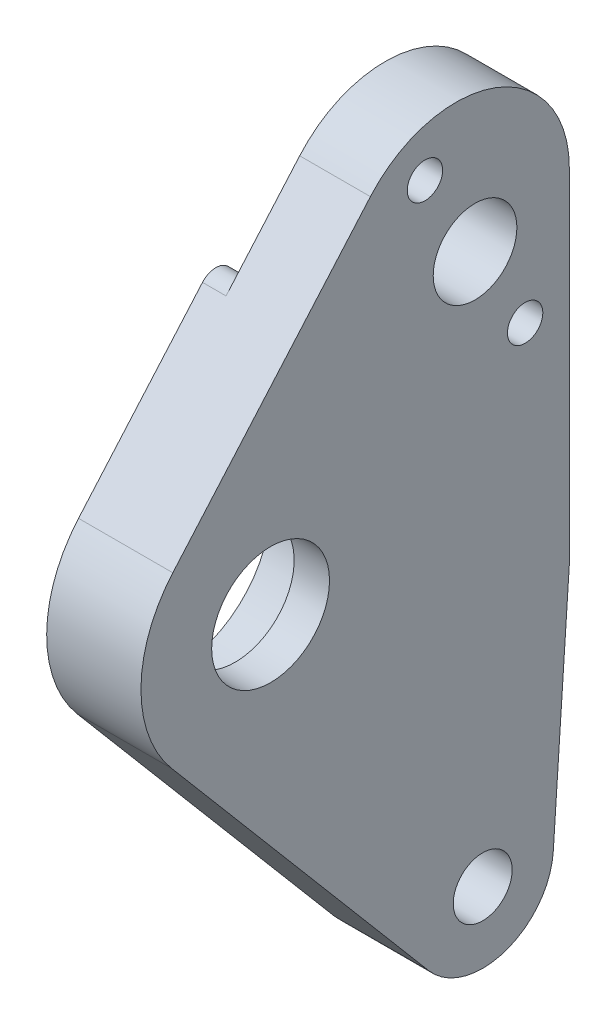
SolidWorks part; units mm, degrees
material "POM Acetal Copolymer"
ref_plane "Front Plane" through (0, 0, 0) normal (0, 0, 1) x (1, 0, 0)
ref_plane "Top Plane" through (0, 0, 0) normal (0, 1, 0) x (1, 0, 0)
ref_plane "Right Plane" through (0, 0, 0) normal (1, 0, 0) x (0, 0, -1)
sketch "Sketch27" plane through (0, 0, 0) normal (1, 0, 0) x (0, 0, -1)
  line L0 (3.7034, 44.2227) -> (20.4692, 63.4812)
  line L1 (37.3494, 57.163) -> (37.3494, 28)
  line L5 (37.3494, 28) -> (35.9867, 7.6001)
  line L6 (25.4207, 4.1232) -> (3.6046, 29.8925)
  line L8 (0, 0) -> (60, 0) construction
  line L9 (0, 0) -> (0, 58) construction
  line L10 (0, 58) -> (60, 58) construction
  line L11 (60, 0) -> (60, 58) construction
  arc A0 (3.7034, 44.2227) -> (3.6046, 29.8925) centre (12, 37) ccw
  circle A1 centre (29.3494, 55) radius 12.5 construction
  arc A2 (37.3494, 57.163) -> (20.4692, 63.4812) centre (27.7268, 57.163) ccw
  circle A3 centre (29.3494, 55) radius 3.55
  arc A4 (35.9867, 7.6001) -> (25.4207, 4.1232) centre (30, 8) cw
  circle A5 centre (12, 37) radius 5
  circle A6 centre (30, 8) radius 2.5
  dimension "D9" = 6
  dimension "D10" = 5
  dimension "D11" = 28
  dimension "D12" = 10
  dimension "D13" = 11
  dimension "D15" = 25
  dimension "D6" = 25
  dimension "D17" = 7.1
  dimension "D1" = 60
  dimension "D2" = 58
  dimension "D3" = 37
  dimension "D4" = 12
  dimension "D5" = 30
  dimension "D7" = 8
  dimension "D8" = 18
  dimension "D16" = 8
extrude "Boss-Extrude1" add sketch "Sketch27" along normal blind 8
hole_wizard "Tap Drill for M3 Tap2" positions "Sketch45" profile "Sketch44" hole size "M3" standard "ISO"
sketch "Sketch45" plane through (0, 0, -37.3494) normal (0, 0, -1) x (-1, 0, 0)
  line L3 (-8, 28) -> (0, 28) construction
  line L4 (-8, 28) -> (-8, 57.163) construction
  point P0 (-5, 44)
  point P7 (-5, 32)
  dimension "D1" = 4
  dimension "D2" = 3
  dimension "D3" = 12
sketch "Sketch44" plane through (5, 44, -37.3494) normal (1, 0, 0) x (0, 1, 0)
  line L0 (0, 0) -> (0, 10.7511)
  line L1 (0, 10.7511) -> (1.25, 10)
  line L2 (1.25, 10) -> (1.25, 0)
  line L5 (1.25, 0) -> (0, 0)
  line L10 (0, 10.7511) -> (-1.25, 10) construction
  line L11 (0, -6.35) -> (0, 107.95) construction
  dimension "Hole Dia." = 2.5
  dimension "Hole Depth" = 10
  dimension "Drill Angle" = 118
sketch "Sketch47" plane through (0, 0, 0) normal (-1, 0, 0) x (0, 0, 1)
  circle A0 centre (-12, 37) radius 7.99
  dimension "D1" = 15.98
extrude "Cut-Extrude8" cut sketch "Sketch47" against normal blind 5
sketch "Sketch48" plane through (0, 0, 0) normal (-1, 0, 0) x (0, 0, 1)
  line L0 (-37.3494, 28) -> (-37.3494, 57.163) construction
  line L1 (-20.4692, 63.4812) -> (-3.7034, 44.2227) construction
  line L2 (-37.3494, 42.6004) -> (-37.3494, 72.6467)
  line L3 (-37.3494, 72.6467) -> (-14.2217, 72.6467)
  line L4 (-14.2217, 72.6467) -> (-14.2217, 56.3048)
  arc A0 (-35.1529, 43.9289) -> (-16.8526, 55.2856) centre (-29.3494, 55) ccw
  arc A1 (-35.1529, 43.9289) -> (-37.3494, 42.6004) centre (-35.8494, 42.6004) ccw
  arc A2 (-16.8526, 55.2856) -> (-14.2217, 56.3048) centre (-15.353, 55.3199) cw
  dimension "D1" = 12.5
  dimension "D2" = 1.5
  dimension "D3" = 1.5
extrude "Cut-Extrude10" cut sketch "Sketch48" against normal blind 2
sketch "Sketch49" plane through (2, 0, 0) normal (-1, 0, 0) x (0, 0, 1)
  line L0 (-29.3494, 55) -> (-25.0994, 62.3612) construction
  line L1 (-33.5994, 47.6388) -> (-29.3494, 55) construction
  line L2 (-29.3494, 55) -> (-29.3494, 62.9962) construction
  circle A0 centre (-33.5994, 47.6388) radius 1.5
  circle A1 centre (-25.0994, 62.3612) radius 1.5
  circle A2 centre (-29.3494, 55) radius 3.55 construction
  dimension "D2" = 8.5
  dimension "D3" = 3
  dimension "D1" = 30
extrude "Cut-Extrude11" cut sketch "Sketch49" against normal up to next
